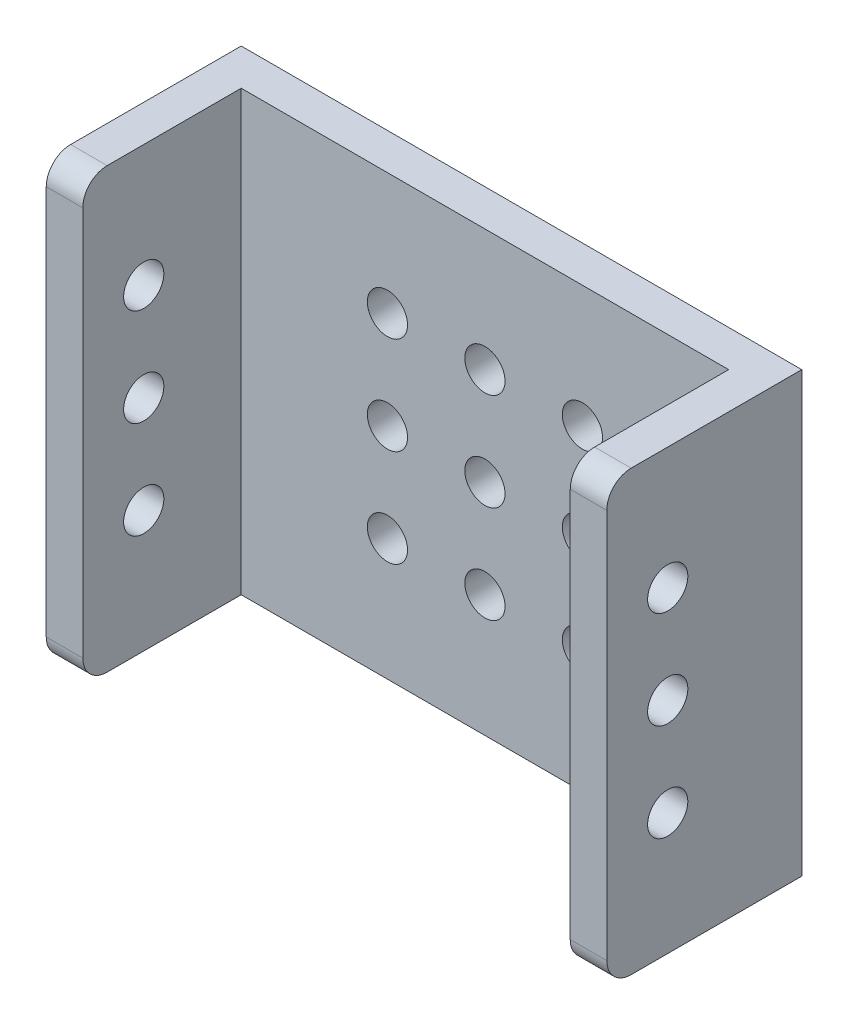
SolidWorks part; units mm, degrees
ref_plane "前视基准面" through (0, 0, 0) normal (0, 0, 1) x (1, 0, 0)
ref_plane "上视基准面" through (0, 0, 0) normal (0, 1, 0) x (1, 0, 0)
ref_plane "右视基准面" through (0, 0, 0) normal (1, 0, 0) x (0, 0, -1)
sketch "草图2" plane through (0, 0, 0) normal (0, 0, 1) x (1, 0, 0)
  line L0 (0, 0) -> (46, 0)
  line L1 (0, 0) -> (0, 36)
  line L2 (46, 0) -> (46, 36)
  line L3 (0, 36) -> (46, 36)
  line L4 (0, 36) -> (46, 0)
  circle A0 centre (23, 18) radius 1.65
  circle A1 centre (23, 18) radius 8
  circle A2 centre (31, 18) radius 1.65
  circle A3 centre (23, 26) radius 1.65
  circle A4 centre (31, 26) radius 1.65
  circle A5 centre (15, 26) radius 1.65
  circle A6 centre (31, 10) radius 1.65
  circle A7 centre (15, 18) radius 1.65
  circle A8 centre (23, 10) radius 1.65
  circle A9 centre (15, 10) radius 1.65
extrude "凸台-拉伸1" add sketch "草图2" along normal blind 3 contours A8 A1 A7 L4 A5 L1 L0 A6 A9 | A6 L4 L2 L3 A5 A1 A3 A2 A4 | A3 A1 L4 A0 A2 | A8 A1 L4 A0 A7
sketch "草图3" plane through (0, 0, 3) normal (0, 0, 1) x (1, 0, 0)
  line L0 (0, 36) -> (0, 0)
  line L1 (0, 36) -> (3, 36)
  line L2 (0, 0) -> (3, 0)
  line L3 (3, 36) -> (3, 0)
  line L4 (46, 0) -> (46, 36)
  line L5 (46, 0) -> (43, 0)
  line L6 (46, 36) -> (43, 36)
  line L7 (43, 0) -> (43, 36)
extrude "凸台-拉伸2" add sketch "草图3" along normal blind 13
sketch "草图4" plane through (0, 0, 0) normal (1, 0, 0) x (0, 0, -1)
  line L0 (0, 0) -> (0, 36)
  line L1 (0, 0) -> (-11, 0)
  line L2 (0, 36) -> (-11, 36)
  line L3 (-11, 0) -> (-11, 36)
  circle A0 centre (-11, 18) radius 1.65
  circle A1 centre (-11, 26) radius 1.65
  circle A2 centre (-11, 10) radius 1.65
extrude "切除-拉伸1" cut sketch "草图4" along normal blind 50 contours L3 A1 | L3 A1 | L3 A0 | L3 A0 | L3 A2 | L3 A2
fillet "圆角1" radius 2 4 edges at (44.5, 0, 16) (44.5, 36, 16) (1.5, 36, 16) (1.5, 0, 16)
